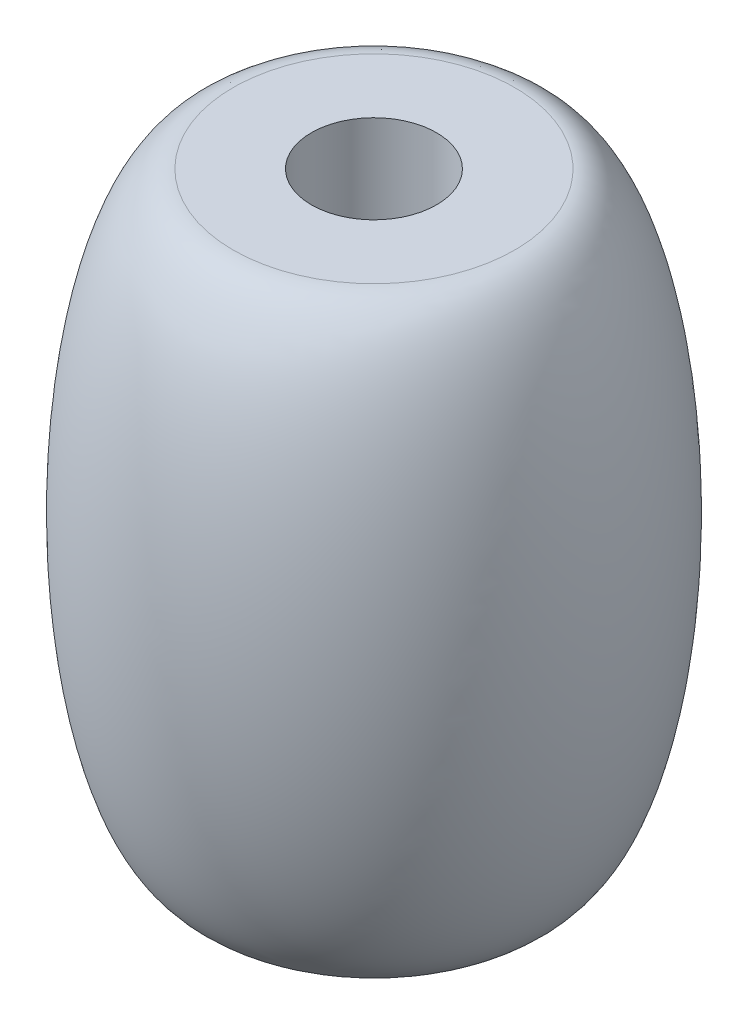
SolidWorks part; units mm, degrees
ref_plane "Front" through (0, 0, 0) normal (0, 0, 1) x (1, 0, 0)
ref_plane "Top" through (0, 0, 0) normal (0, 1, 0) x (1, 0, 0)
ref_plane "Right" through (0, 0, 0) normal (1, 0, 0) x (0, 0, -1)
sketch "草图1" plane through (0, 0, 0) normal (0, 0, 1) x (1, 0, 0)
  line L0 (0, 14.8626) -> (0, -20.7155) construction
  line L1 (-2, 9.5) -> (-2, -9.5)
  line L2 (-2, -9.5) -> (-4.5, -9.5)
  line L4 (-4.5, 9.5) -> (-2, 9.5)
  line L5 (-2, 0) -> (-13.4226, 0) construction
  ellipse E0 centre (-4.5, 0) end of major axis (-4.5, -9.5) minor radius 2.9016 (-4.5, 9.5) -> (-4.5, -9.5) ccw
  point P6 (-7.7621, -0.4207)
  point P8 (0, 0)
  point P9 (0, 0)
  point P11 (-6.5, 0)
  point P16 (0, 0)
  point P17 (-7.4016, 0)
  dimension "D1" = 19
  dimension "D2" = 2
  dimension "D3" = 6.5
revolve "旋转2" add sketch "草图1" angle 360 about L0
scale "缩放比例1" scale about centroid uniform scaling yes scale factor 0.683
